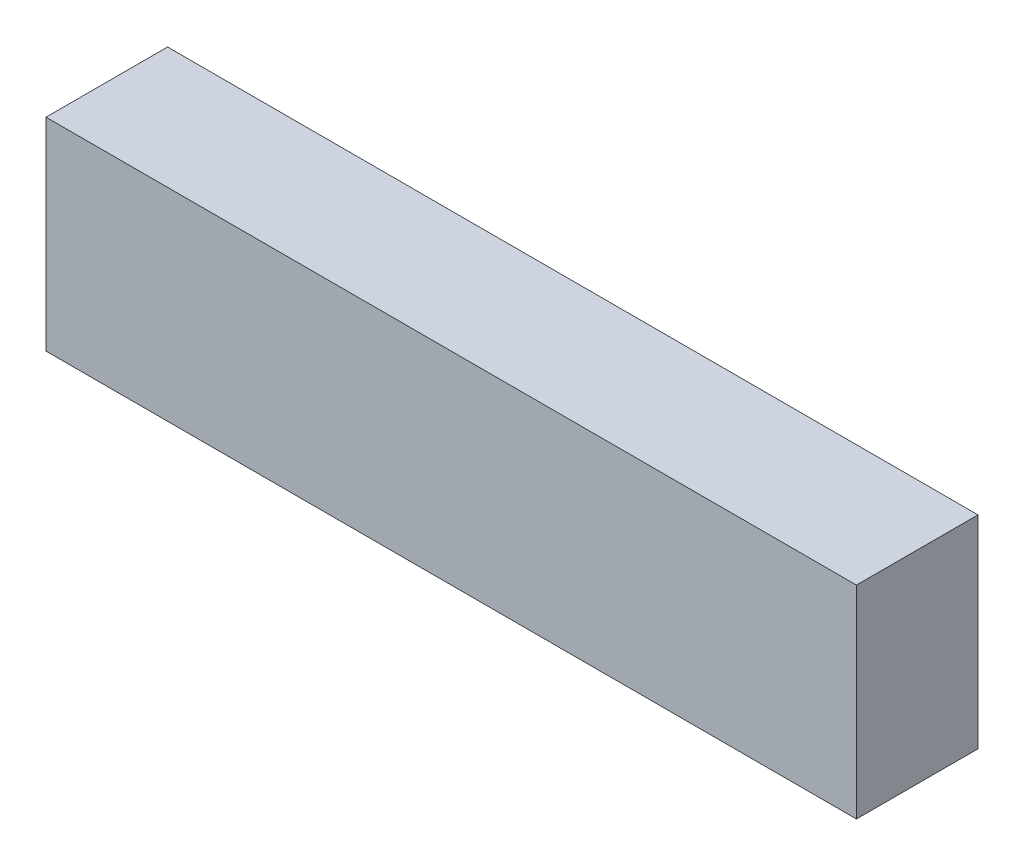
SolidWorks part; units mm, degrees
ref_plane "Спереди" through (0, 0, 0) normal (0, 0, 1) x (1, 0, 0)
ref_plane "Сверху" through (0, 0, 0) normal (0, 1, 0) x (1, 0, 0)
ref_plane "Справа" through (0, 0, 0) normal (1, 0, 0) x (0, 0, -1)
sketch "Эскиз1" plane through (0, 0, 0) normal (0, 0, 1) x (1, 0, 0)
  line L1 (-100, -25) -> (100, -25)
  line L2 (-100, -25) -> (-100, 25)
  line L3 (-100, 25) -> (100, 25)
  line L4 (100, -25) -> (100, 25)
  line L5 (-100, -25) -> (100, 25) construction
  line L6 (-100, 25) -> (100, -25) construction
  point P0 (0, 0)
  dimension "D1" = 200
  dimension "D2" = 50
extrude "Бобышка-Вытянуть1" add sketch "Эскиз1" along normal blind 30
